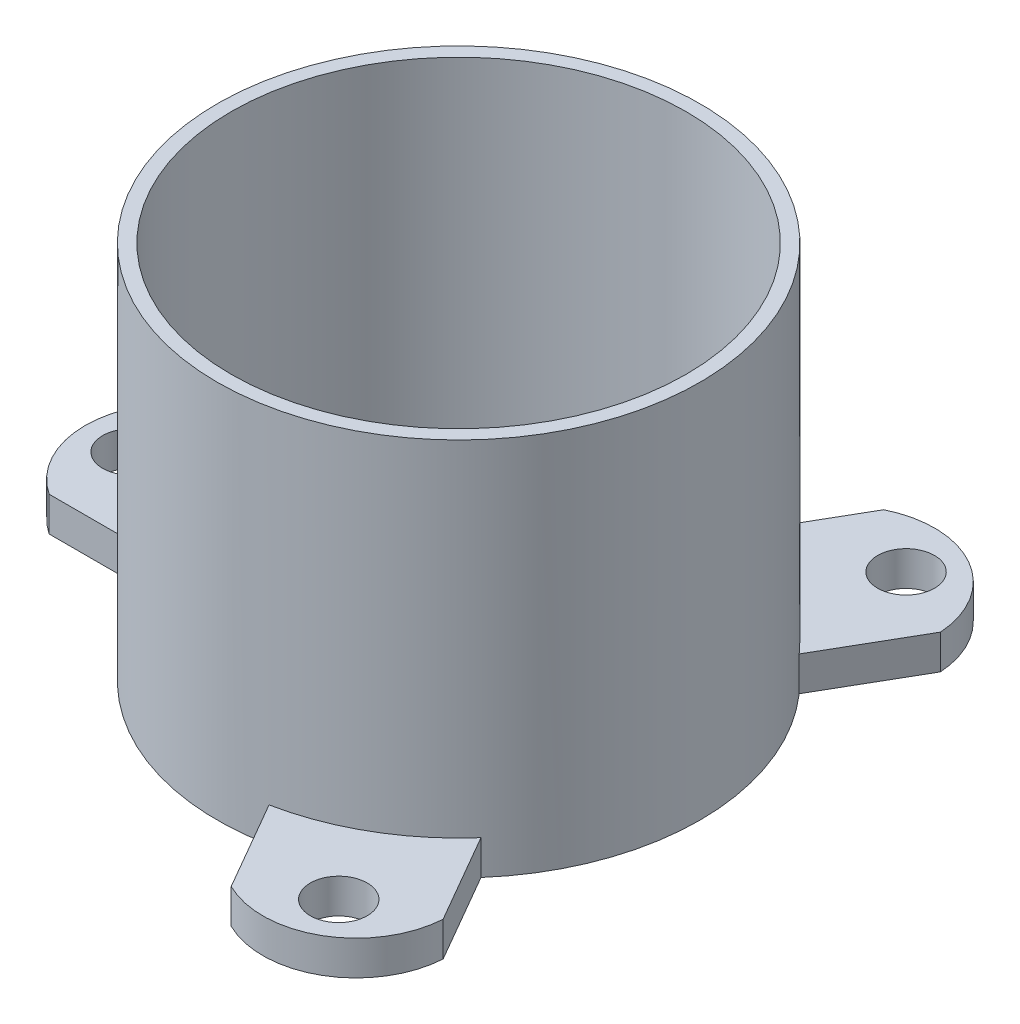
SolidWorks part; units mm, degrees
ref_plane "Plano frontal" through (0, 0, 0) normal (0, 0, 1) x (1, 0, 0)
ref_plane "Plano superior" through (0, 0, 0) normal (0, 1, 0) x (1, 0, 0)
ref_plane "Plano direito" through (0, 0, 0) normal (1, 0, 0) x (0, 0, -1)
sketch "Esboço4" plane through (0, 0, 0) normal (0, 1, 0) x (1, 0, 0)
  line L0 (0, 0) -> (-60.407, 0) construction
  line L1 (-21.6654, 0) -> (-83.4779, 0) construction
  line L2 (-19.2571, -4.5) -> (-13.2571, -4.5)
  line L4 (-19.2571, 4.5) -> (-13.2571, 4.5)
  line L6 (-19.2571, -4.5) -> (-13.2571, 4.5) construction
  line L7 (-19.2571, 4.5) -> (-13.2571, -4.5) construction
  line L8 (13.5257, 14.4271) -> (10.5257, 9.231)
  line L9 (5.7314, 18.9271) -> (2.7314, 13.731)
  line L10 (13.5257, 14.4271) -> (2.7314, 13.731) construction
  line L11 (5.7314, 18.9271) -> (10.5257, 9.231) construction
  line L12 (0, 0) -> (15, 25.9808) construction
  line L13 (5.7314, -18.9271) -> (2.7314, -13.731)
  line L14 (13.5257, -14.4271) -> (10.5257, -9.231)
  line L15 (5.7314, -18.9271) -> (10.5257, -9.231) construction
  line L16 (13.5257, -14.4271) -> (2.7314, -13.731) construction
  line L17 (0, 0) -> (15, -25.9808) construction
  line L18 (8.1285, -14.079) -> (30.2035, -52.314) construction
  line L19 (8.1285, 14.079) -> (30.2035, 52.314) construction
  arc A0 (-13.2571, -4.5) -> (2.7314, -13.731) centre (0, 0) ccw
  arc A1 (-19.2571, 4.5) -> (-19.2571, -4.5) centre (-16.2571, 0) ccw
  circle A2 centre (-19, 0) radius 1.65
  circle A3 centre (9.5, 16.4545) radius 1.65
  arc A4 (13.5257, 14.4271) -> (5.7314, 18.9271) centre (8.1285, 14.079) ccw
  circle A5 centre (9.5, -16.4545) radius 1.65
  arc A6 (5.7314, -18.9271) -> (13.5257, -14.4271) centre (8.1285, -14.079) ccw
  arc A7 (10.5257, -9.231) -> (10.5257, 9.231) centre (0, 0) ccw
  arc A8 (2.7314, 13.731) -> (-13.2571, 4.5) centre (0, 0) ccw
  point P3 (-16.2571, 0)
  point P9 (-19, 0)
  point P32 (0, 0)
  dimension "D1" = 14
  dimension "D4" = 3.3
  dimension "D5" = 19
  dimension "D2" = 9
  dimension "D3" = 6
  dimension "D6" = 3
extrude "Ressalto-extrusão2" add sketch "Esboço4" along normal blind 2
sketch "Esboço5" plane through (0, 2, 0) normal (0, 1, 0) x (1, 0, 0)
  circle A0 centre (0, 0) radius 14
extrude "Ressalto-extrusão3" add sketch "Esboço5" along normal blind 20
sketch "Esboço6" plane through (0, 22, 0) normal (0, 1, 0) x (1, 0, 0)
  circle A0 centre (0, 0) radius 13.2
  dimension "D1" = 26.4
extrude "Corte-extrusão1" cut sketch "Esboço6" against normal blind 20 contours A0
